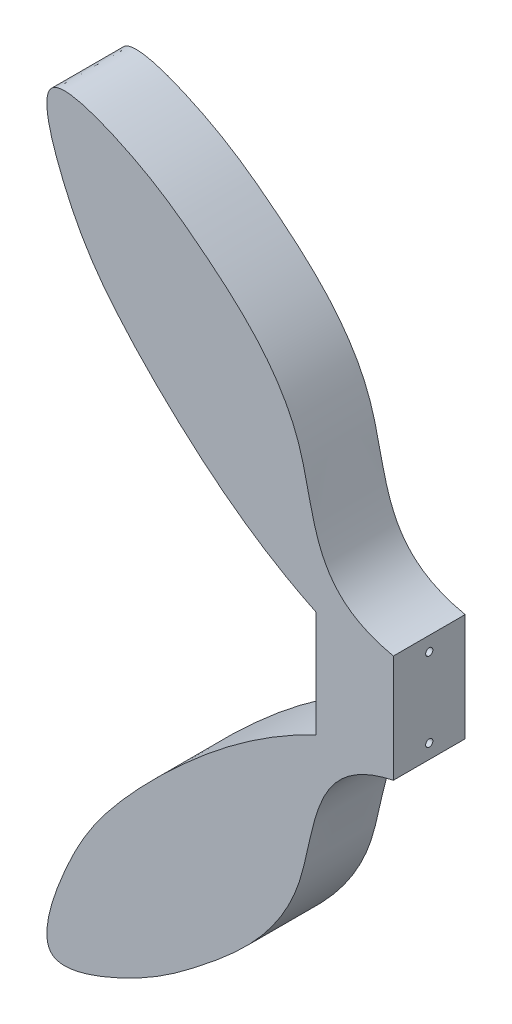
SolidWorks part; units mm, degrees
material "Silicon Rubber"
ref_plane "Front Plane" through (0, 0, 0) normal (0, 0, 1) x (1, 0, 0)
ref_plane "Top Plane" through (0, 0, 0) normal (0, 1, 0) x (1, 0, 0)
ref_plane "Right Plane" through (0, 0, 0) normal (1, 0, 0) x (0, 0, -1)
sketch "Sketch1" plane through (0, 0, 0) normal (0, 0, 1) x (1, 0, 0)
  line L0 (-39.5185, 0) -> (39.5185, 0) construction
  line L1 (15.4866, 15) -> (15.4866, -15)
  line L3 (-6.0615, -14.8109) -> (-6.0615, 14.8109)
  spline S0 degree 3 poles (15.4866, 15) (-8.2715, 20.0263) (-4.7175, 45.5527) (-20.8581, 72.3408) (-39.4551, 87.9535) (-55.8517, 99.6809) (-86.0285, 110.8484) (-75.5823, 78.2656) (-63.5553, 60.4904) (-39.268, 35.6798) (-20.3237, 21.6467) (-6.0615, 14.8109) knots 0 0 0 0 0.186871 0.261406 0.356661 0.456593 0.531301 0.612808 0.720983 0.820296 1 1 1 1
  spline S1 degree 3 poles (15.4866, -15) (-8.2715, -20.0263) (-4.7175, -45.5527) (-20.8581, -72.3408) (-39.4551, -87.9535) (-55.8517, -99.6809) (-86.0285, -110.8484) (-75.5823, -78.2656) (-63.5553, -60.4904) (-39.268, -35.6798) (-20.3237, -21.6467) (-6.0615, -14.8109) knots 0 0 0 0 0.186871 0.261406 0.356661 0.456593 0.531301 0.612808 0.720983 0.820296 1 1 1 1
  point P2 (-0.0913, 23.0541)
  point P3 (0, 0)
  point P4 (-80.4577, 95.2409)
  dimension "D2" = 30
  dimension "D1" = 15
extrude "Boss-Extrude1" add sketch "Sketch1" along normal mid plane 20
sketch "Sketch2" plane through (15.4866, 0, 0) normal (1, 0, 0) x (0, 0, -1)
  line L0 (0, 15) -> (0, -15) construction
  line L1 (-10, 15) -> (10, 15) construction
  line L2 (-10, -15) -> (10, -15) construction
  line L3 (-33.8285, 0) -> (36.2261, 0) construction
  circle A0 centre (0, 11) radius 1
  circle A1 centre (0, -11) radius 1
  dimension "D1" = 2
  dimension "D2" = 11
extrude "Cut-Extrude1" cut sketch "Sketch2" against normal blind 10
